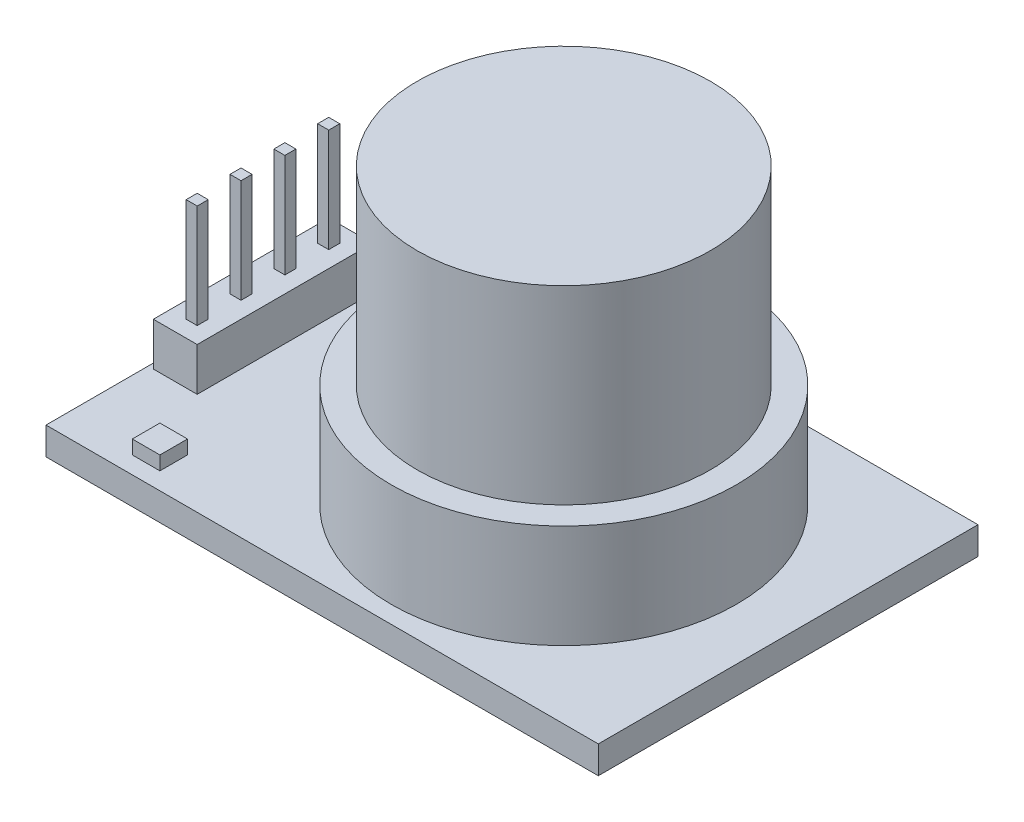
SolidWorks part; units mm, degrees
ref_plane "Front Plane" through (0, 0, 0) normal (0, 0, 1) x (1, 0, 0)
ref_plane "Top Plane" through (0, 0, 0) normal (0, 1, 0) x (1, 0, 0)
ref_plane "Right Plane" through (0, 0, 0) normal (1, 0, 0) x (0, 0, -1)
sketch "SK PCB" plane through (0, 0, 0) normal (0, 1, 0) x (1, 0, 0)
  line L1 (0, 22) -> (32, 22)
  line L2 (0, 22) -> (0, 0)
  line L3 (0, 0) -> (32, 0)
  line L4 (32, 22) -> (32, 0)
extrude "PCB" add sketch "SK PCB" along normal blind 1.6 separate body
sketch "SK Sensor base" plane through (0, 0, 0) normal (0, 1, 0) x (1, 0, 0)
  circle A0 centre (19, 11) radius 10
extrude "Sensor base" add sketch "SK Sensor base" along normal blind 6 from offset 1.6 separate body
sketch "SK Sensor mesh" plane through (0, 0, 0) normal (0, 1, 0) x (1, 0, 0)
  circle A0 centre (19, 11) radius 8.5
extrude "Sensor mesh" add sketch "SK Sensor mesh" along normal blind 11 from offset 7.6 separate body
sketch "SK Header 4 pin" plane through (0, 0, 0) normal (0, 1, 0) x (1, 0, 0)
  line L1 (0.3, 16.08) -> (2.84, 16.08)
  line L2 (0.3, 16.08) -> (0.3, 5.92)
  line L3 (0.3, 5.92) -> (2.84, 5.92)
  line L4 (2.84, 16.08) -> (2.84, 5.92)
extrude "Header 4 pin" add sketch "SK Header 4 pin" along normal blind 2.5 from offset 1.6 separate body
sketch "SK Header pins" plane through (0, 0, 0) normal (0, 1, 0) x (1, 0, 0)
  line L1 (1.25, 15.13) -> (1.89, 15.13)
  line L2 (1.25, 15.13) -> (1.25, 14.49)
  line L3 (1.25, 14.49) -> (1.89, 14.49)
  line L4 (1.89, 15.13) -> (1.89, 14.49)
  line L6 (1.25, 12.59) -> (1.89, 12.59)
  line L7 (1.25, 12.59) -> (1.25, 11.95)
  line L8 (1.25, 11.95) -> (1.89, 11.95)
  line L9 (1.89, 12.59) -> (1.89, 11.95)
  line L11 (1.25, 10.05) -> (1.89, 10.05)
  line L12 (1.25, 10.05) -> (1.25, 9.41)
  line L13 (1.25, 9.41) -> (1.89, 9.41)
  line L14 (1.89, 10.05) -> (1.89, 9.41)
  line L16 (1.25, 7.51) -> (1.89, 7.51)
  line L17 (1.25, 7.51) -> (1.25, 6.87)
  line L18 (1.25, 6.87) -> (1.89, 6.87)
  line L19 (1.89, 7.51) -> (1.89, 6.87)
extrude "Header pins" add sketch "SK Header pins" along normal blind 6 from offset 4.1 separate body
sketch "SK LEDs" plane through (0, 0, 0) normal (0, 1, 0) x (1, 0, 0)
  line L1 (4, 21) -> (5.6, 21)
  line L2 (4, 21) -> (4, 19.4)
  line L3 (4, 19.4) -> (5.6, 19.4)
  line L4 (5.6, 21) -> (5.6, 19.4)
  line L6 (4, 2.6) -> (5.6, 2.6)
  line L7 (4, 2.6) -> (4, 1)
  line L8 (4, 1) -> (5.6, 1)
  line L9 (5.6, 2.6) -> (5.6, 1)
extrude "LEDs" add sketch "SK LEDs" along normal blind 0.8 from offset 1.6 separate body
